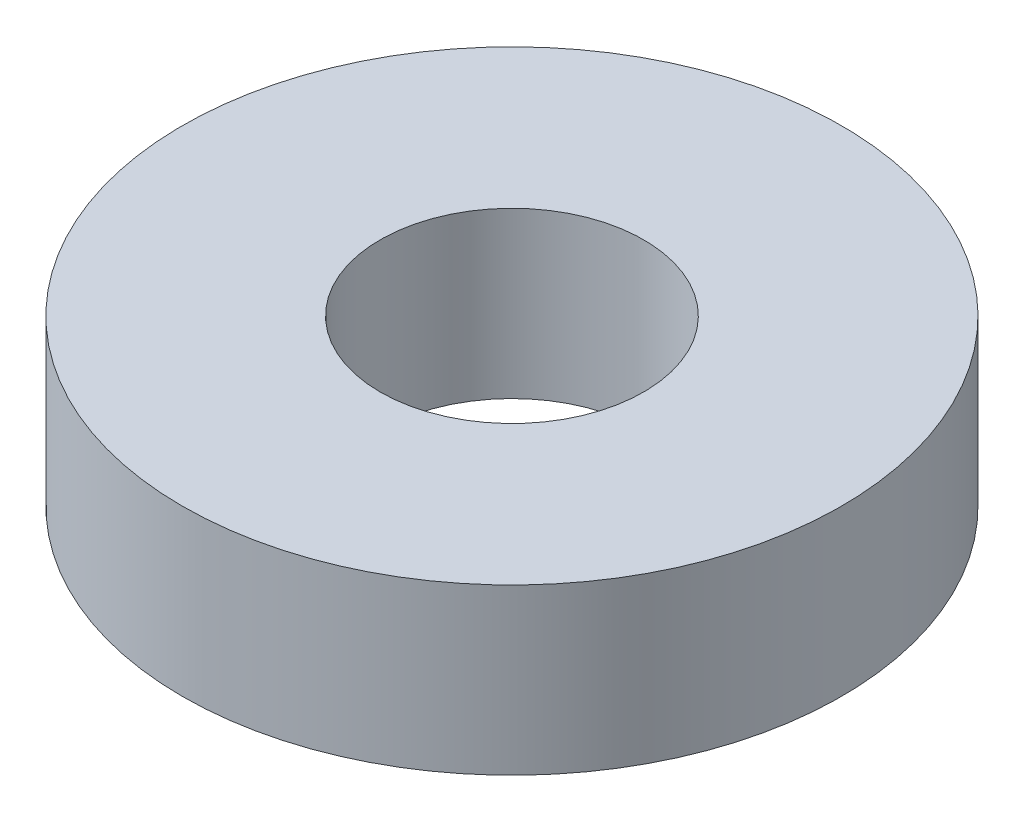
SolidWorks part; units mm, degrees
ref_plane "Front Plane" through (0, 0, 0) normal (0, 0, 1) x (1, 0, 0)
ref_plane "Top Plane" through (0, 0, 0) normal (0, 1, 0) x (1, 0, 0)
ref_plane "Right Plane" through (0, 0, 0) normal (1, 0, 0) x (0, 0, -1)
sketch "Sketch1" plane through (0, 0, 0) normal (0, 1, 0) x (1, 0, 0)
  circle A0 centre (0, 0) radius 10
  circle A1 centre (0, 0) radius 4
  dimension "D1" = 8
  dimension "D2" = 20
extrude "Boss-Extrude1" add sketch "Sketch1" along normal blind 5
